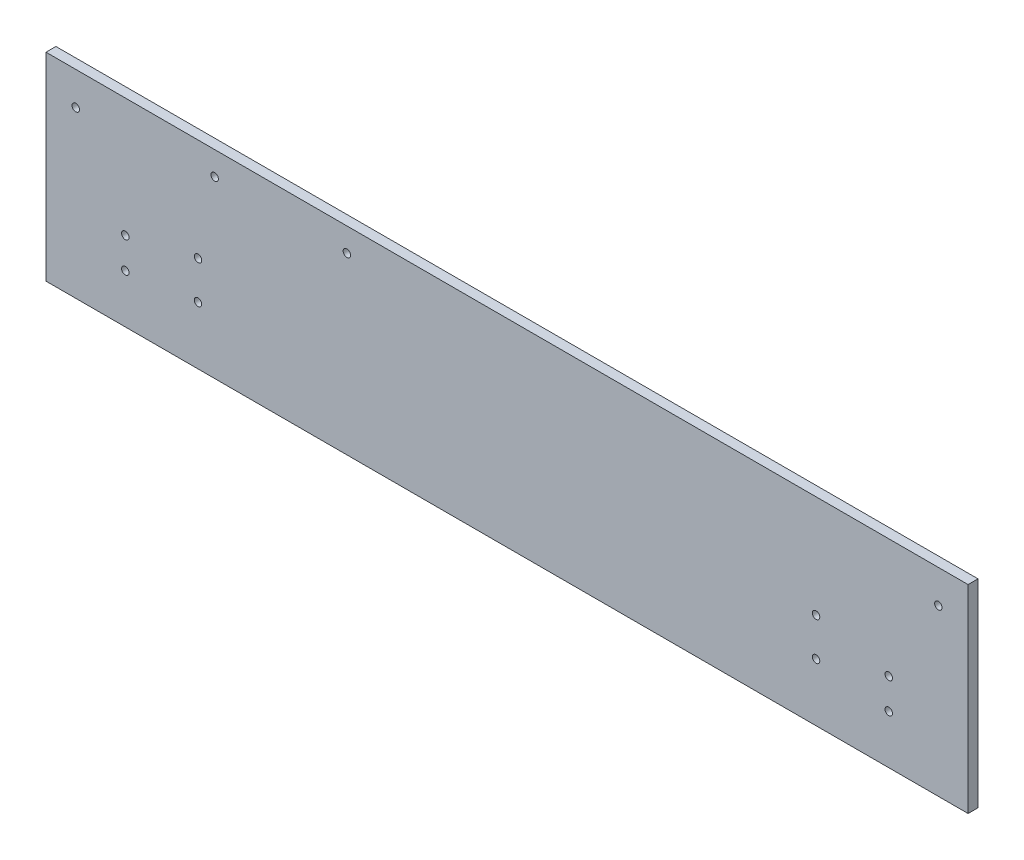
SolidWorks part; units mm, degrees
material "Pino"
ref_plane "Piano frontale" through (0, 0, 0) normal (0, 0, 1) x (1, 0, 0)
ref_plane "Piano superiore" through (0, 0, 0) normal (0, 1, 0) x (1, 0, 0)
ref_plane "Piano destro" through (0, 0, 0) normal (1, 0, 0) x (0, 0, -1)
sketch "Schizzo1" plane through (0, 0, 0) normal (0, 0, 1) x (1, 0, 0)
  line L1 (-279, 60) -> (279, 60)
  line L2 (-279, 60) -> (-279, -60)
  line L3 (-279, -60) -> (279, -60)
  line L4 (279, 60) -> (279, -60)
  line L5 (-279, 60) -> (279, -60) construction
  line L6 (-279, -60) -> (279, 60) construction
  point P4 (0, 0)
  dimension "D1" = 558
  dimension "D2" = 120
extrude "Estrusione-Estrusione1" add sketch "Schizzo1" along normal blind 6
sketch "Schizzo2" plane through (0, 0, 0) normal (0, 0, -1) x (-1, 0, 0)
  line L0 (-187, -2) -> (-187, -25) construction
  line L1 (187, -2) -> (187, -25) construction
  line L2 (279, 60) -> (279, -60) construction
  line L4 (279, -60) -> (-279, -60) construction
  line L5 (-279, -60) -> (-279, 60) construction
  line L6 (176.9257, 45.7) -> (96.9257, 45.7) construction
  line L7 (-279, 60) -> (279, 60) construction
  line L8 (279, 60) -> (279, -60) construction
  circle A0 centre (-231, -12) radius 2.25
  circle A1 centre (-231, -30.5) radius 2.25
  circle A2 centre (231, -12) radius 2.25
  circle A3 centre (231, -30.5) radius 2.25
  circle A5 centre (-261, 40) radius 2.25
  circle A7 centre (261, 40) radius 2.25
  circle A8 centre (-187, -25) radius 2.25
  circle A9 centre (-187, -2) radius 2.25
  circle A10 centre (187, -25) radius 2.25
  circle A11 centre (187, -2) radius 2.25
  circle A12 centre (176.9257, 45.7) radius 2.25
  circle A13 centre (96.9257, 45.7) radius 2.25
  point P36 (187, -13.5)
  dimension "D1" = 4.5
  dimension "D7" = 14.3
  dimension "D2" = 92
  dimension "D3" = 58
  dimension "D4" = 23
  dimension "D5" = 92
  dimension "D6" = 58
  dimension "D8" = 102.0743
  dimension "D9" = 80
extrude "Taglio-Estrusione1" cut sketch "Schizzo2" against normal blind 10
